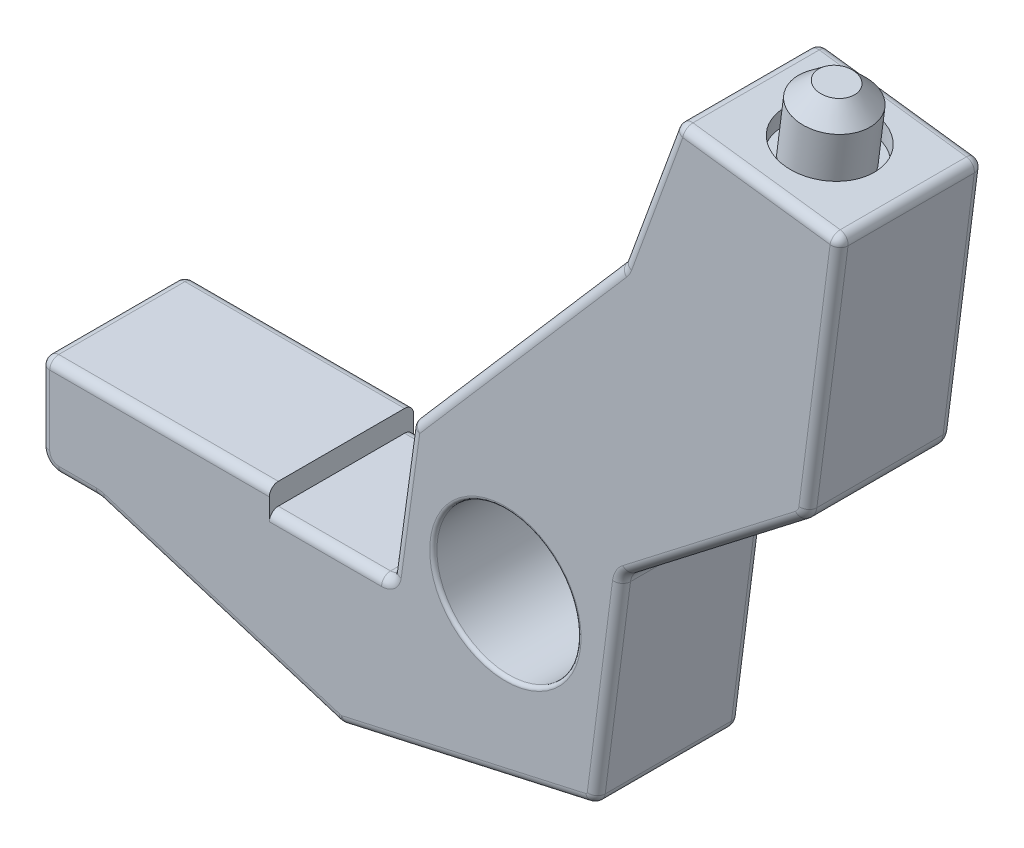
SolidWorks part; units mm, degrees
ref_plane "정면" through (0, 0, 0) normal (0, 0, 1) x (1, 0, 0)
ref_plane "윗면" through (0, 0, 0) normal (0, 1, 0) x (1, 0, 0)
ref_plane "우측면" through (0, 0, 0) normal (1, 0, 0) x (0, 0, -1)
sketch "스케치1" plane through (0, 0, 0) normal (0, 0, 1) x (1, 0, 0)
  line L0 (18.503, 25.7104) -> (16.7742, 12.2695)
  line L1 (16.3935, 11.6055) -> (6.819, 4.2134)
  line L2 (6.4383, 3.5494) -> (5.0369, -7.3456)
  line L4 (-9.3307, -10.8517) -> (-22.3964, -6.8075)
  line L5 (-22.6921, -6.7628) -> (-24.7735, -6.7628)
  line L6 (-25.7735, -5.7628) -> (-25.7735, -1.8955)
  line L7 (-25.2735, -1.3955) -> (-13.0927, -1.3955)
  line L8 (-13.0927, -1.3955) -> (-13.0927, -2.5895)
  line L9 (-6.2748, -2.0715) -> (-5.2459, 5.3872)
  line L10 (-5.1285, 5.6462) -> (6.3479, 18.8962)
  line L11 (6.5316, 19.2084) -> (9.3699, 26.996)
  line L12 (9.9035, 27.3207) -> (18.0709, 26.2701)
  line L13 (-13.0927, -2.5895) -> (-6.8692, -2.5895)
  line L14 (4.5727, -7.8546) -> (-8.9556, -10.8786)
  arc A0 (4.5727, -7.8546) -> (5.0369, -7.3456) centre (4.4418, -7.269) ccw
  circle A1 centre (0, 0) radius 4
  arc A2 (-25.7735, -1.8955) -> (-25.2735, -1.3955) centre (-25.2735, -1.8955) cw
  arc A3 (-5.2459, 5.3872) -> (-5.1285, 5.6462) centre (-4.7506, 5.3188) cw
  arc A4 (18.503, 25.7104) -> (18.0709, 26.2701) centre (18.0071, 25.7742) ccw
  arc A5 (9.3699, 26.996) -> (9.9035, 27.3207) centre (9.8397, 26.8247) cw
  arc A6 (-24.7735, -6.7628) -> (-25.7735, -5.7628) centre (-24.7735, -5.7628) cw
  arc A7 (-22.3964, -6.8075) -> (-22.6921, -6.7628) centre (-22.6921, -7.7628) ccw
  arc A8 (-9.1636, -10.8881) -> (-9.3307, -10.8517) centre (-9.035, -9.8964) cw
  arc A9 (-8.9556, -10.8786) -> (-9.1636, -10.8881) centre (-9.0865, -10.2931) cw
  arc A10 (6.819, 4.2134) -> (6.4383, 3.5494) centre (7.4301, 3.4218) ccw
  arc A11 (6.3479, 18.8962) -> (6.5316, 19.2084) centre (5.592, 19.5509) ccw
  arc A12 (16.7742, 12.2695) -> (16.3935, 11.6055) centre (15.7824, 12.3971) cw
  arc A13 (-6.2748, -2.0715) -> (-6.8692, -2.5895) centre (-6.8692, -1.9895) cw
  dimension "D1" = 0.6
  dimension "D2" = 8
  dimension "D3" = 0.5
  dimension "D4" = 1
  dimension "D5" = 0.6
  dimension "D6" = 0.6
extrude "보스-돌출1" add sketch "스케치1" along normal blind 8
sketch "스케치2" plane through (3.6181, 28.1291, 0) normal (0.1276, 0.9918, 0) x (0.9918, -0.1276, 0)
  line L0 (6.3371, 0) -> (14.5718, -8) construction
  circle A0 centre (10.4545, -4) radius 2
extrude "보스-돌출2" add sketch "스케치2" along normal blind 3
chamfer "모따기1" distance 1 angle 45 1 edges at (12.3863, 30.026, 4)
sketch "스케치3" plane through (3.6181, 28.1291, 0) normal (0.1276, 0.9918, 0) x (0.9918, -0.1276, 0)
  circle A0 centre (10.4545, -4) radius 2.5
  circle A1 centre (10.4545, -4) radius 2 construction
  circle A2 centre (10.4545, -4) radius 2
fillet "필렛1" radius 0.2 2 edges at (4, 0, 0) (4, 0, 8)
extrude "컷-돌출1" cut sketch "스케치3" against normal blind 1
fillet "필렛2" radius 0.5 52 edges at (-19.1831, -1.3955, 8) (-25.6271, -1.5419, 8) (-25.7735, -3.8292, 8) (-25.4806, -6.4699, 8) (-23.7328, -6.7628, 8) (-22.5426, -6.7741, 8) (-15.8636, -8.8296, 8) (-9.2479, -10.8735, 8) (5.7376, -1.8981, 8) (6.5626, 3.9193, 8) (-9.9809, -2.5895, 8) (-6.475, -2.4418, 8) (-5.7603, 1.6579, 8) (-5.206, 5.5252, 8) (0.6097, 12.2712, 8) (6.454, 19.0439, 8) (7.9507, 23.1022, 8) (9.5798, 27.2519, 8) (13.9872, 26.7954, 8) (18.4029, 26.0797, 8) (17.6386, 18.9899, 8) (16.6499, 11.8996, 8) (-19.1831, -1.3955, 0) (-25.6271, -1.5419, 0) (-25.7735, -3.8292, 0) (-25.4806, -6.4699, 0) (-23.7328, -6.7628, 0) (-22.5426, -6.7741, 0) (-15.8636, -8.8296, 0) (-9.2479, -10.8735, 0) (5.7376, -1.8981, 0) (6.5626, 3.9193, 0) (-9.9809, -2.5895, 0) (-6.475, -2.4418, 0) (-5.7603, 1.6579, 0) (-5.206, 5.5252, 0) (0.6097, 12.2712, 0) (6.454, 19.0439, 0) (7.9507, 23.1022, 0) (9.5798, 27.2519, 0) (13.9872, 26.7954, 0) (18.4029, 26.0797, 0) (17.6386, 18.9899, 0) (16.6499, 11.8996, 0) (11.6062, 7.9094, 8) (11.6062, 7.9094, 0) (-9.0591, -10.8924, 8) (-2.1914, -9.3666, 8) (4.8851, -7.6733, 8) (-9.0591, -10.8924, 0) (-2.1914, -9.3666, 0) (4.8851, -7.6733, 0)
